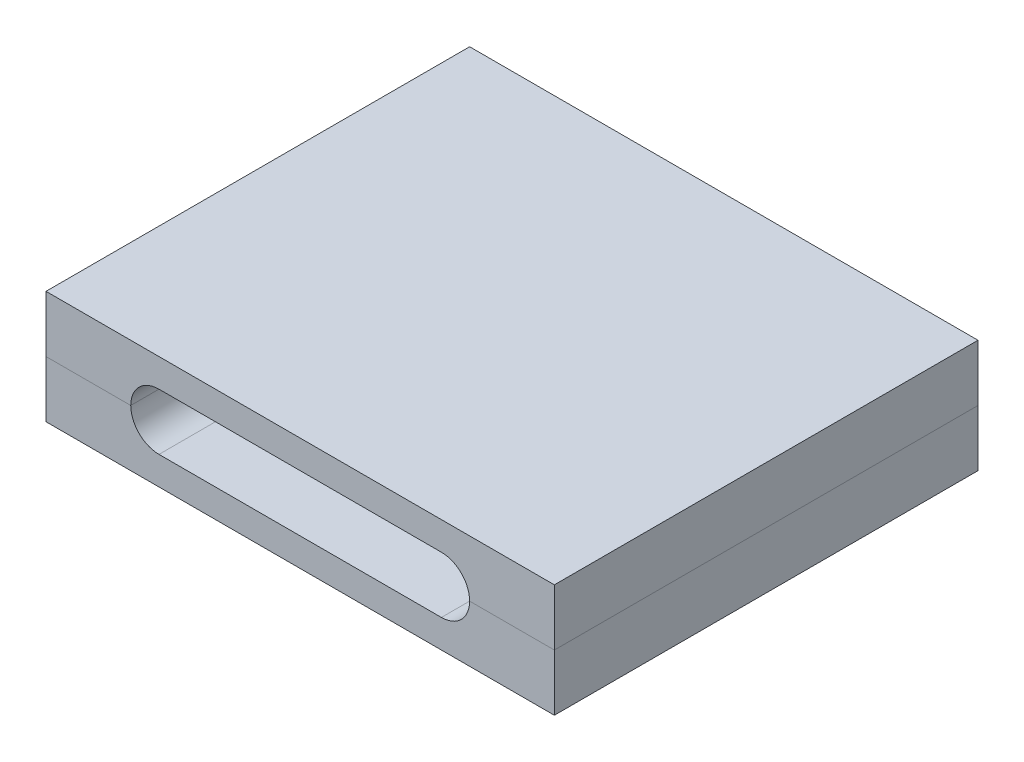
SolidWorks part; units mm, degrees
ref_plane "정면" through (0, 0, 0) normal (0, 0, 1) x (1, 0, 0)
ref_plane "윗면" through (0, 0, 0) normal (0, 1, 0) x (1, 0, 0)
ref_plane "우측면" through (0, 0, 0) normal (1, 0, 0) x (0, 0, -1)
sketch "스케치1" plane through (0, 0, 0) normal (0, 0, 1) x (1, 0, 0)
  line L0 (-5, 0) -> (5, 0) construction
  line L1 (-5, 1) -> (5, 1)
  line L2 (-5, -1) -> (5, -1)
  arc A0 (-5, 1) -> (-5, -1) centre (-5, 0) ccw
  arc A1 (5, -1) -> (5, 1) centre (5, 0) ccw
  point P2 (0, 0)
  dimension "D2" = 1
  dimension "D1" = 10
sketch "스케치2" plane through (0, 0, 0) normal (0, 0, 1) x (1, 0, 0)
  line L1 (-9, 2) -> (9, 2)
  line L2 (-9, 2) -> (-9, -2)
  line L3 (-9, -2) -> (9, -2)
  line L4 (9, 2) -> (9, -2)
  line L5 (-9, 2) -> (9, -2) construction
  line L6 (-9, -2) -> (9, 2) construction
  point P0 (0, 0)
  dimension "D1" = 18
  dimension "D2" = 4
extrude "보스-돌출1" add sketch "스케치2" along normal blind 15
extrude "컷-돌출1" cut sketch "스케치1" along normal blind 15
sketch "스케치3" plane through (0, 0, 15) normal (0, 0, 1) x (1, 0, 0)
  line L0 (9, 0) -> (-9, 0)
  line L1 (9, -2) -> (9, 2) construction
  line L2 (-9, 2) -> (-9, -2) construction
split "분할1" trim tools "스케치3" bodies to split 102 resulting bodies 103 104
